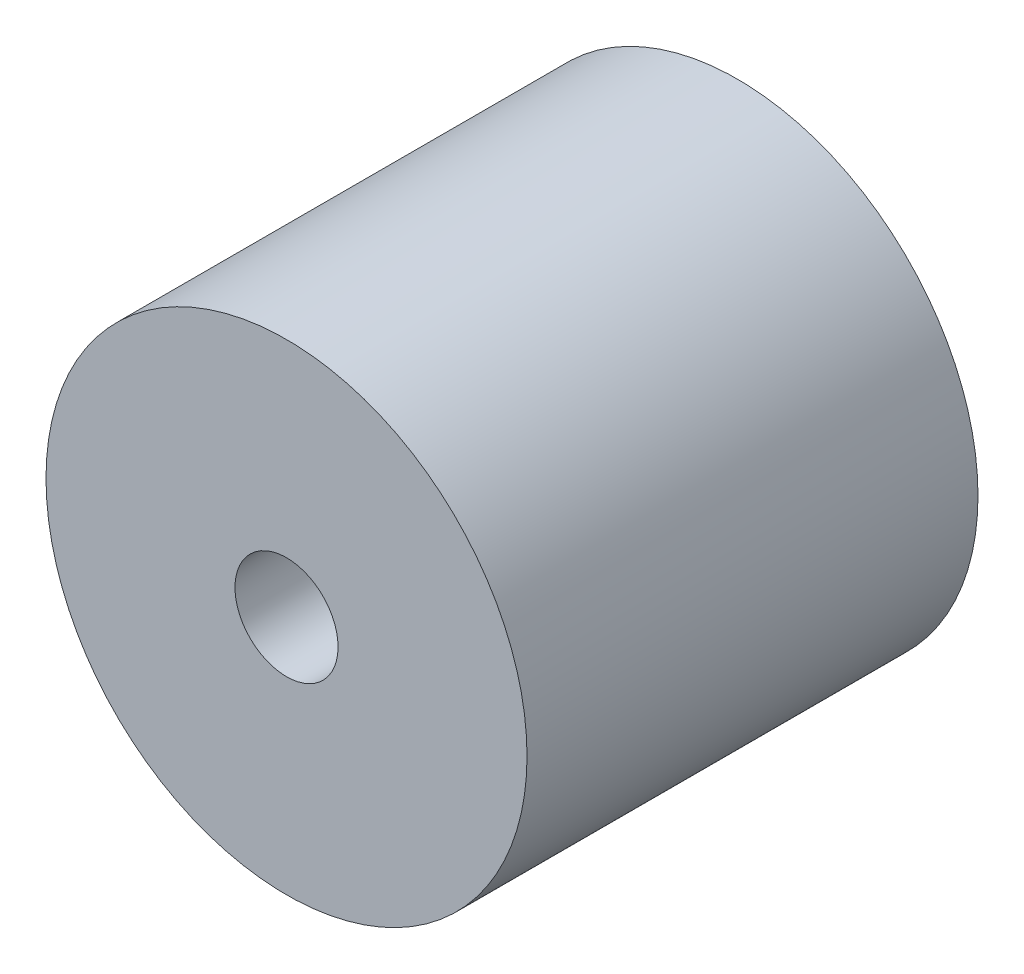
SolidWorks part; units mm, degrees
ref_plane "Alzado" through (0, 0, 0) normal (0, 0, 1) x (1, 0, 0)
ref_plane "Planta" through (0, 0, 0) normal (0, 1, 0) x (1, 0, 0)
ref_plane "Vista lateral" through (0, 0, 0) normal (1, 0, 0) x (0, 0, -1)
sketch "Croquis1" plane through (0, 0, 0) normal (0, 0, 1) x (1, 0, 0)
  circle A0 centre (0, 0) radius 16
  circle A1 centre (0, 0) radius 3.4295
  dimension "D1" = 32
extrude "Saliente-Extruir1" add sketch "Croquis1" along normal blind 30
